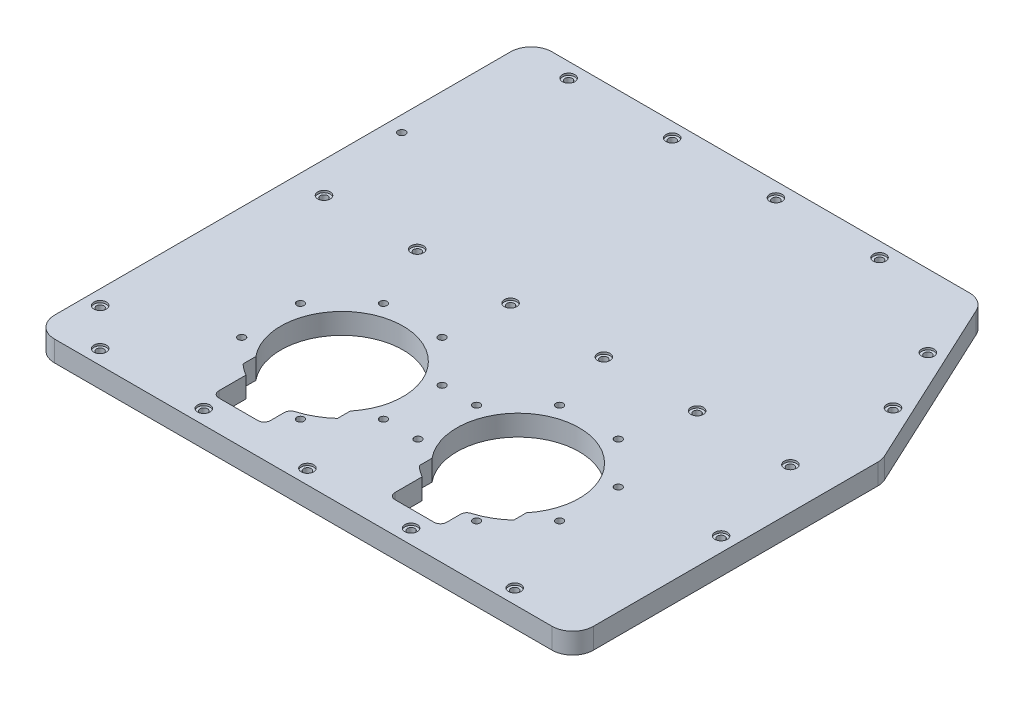
SolidWorks part; units mm, degrees
ref_plane "前视基准面" through (0, 0, 0) normal (0, 0, 1) x (1, 0, 0)
ref_plane "上视基准面" through (0, 0, 0) normal (0, 1, 0) x (1, 0, 0)
ref_plane "右视基准面" through (0, 0, 0) normal (1, 0, 0) x (0, 0, -1)
other "Configuration Table"
sketch "草图1" plane through (0, 0, 0) normal (0, 1, 0) x (1, 0, 0)
  line L0 (10, 0) -> (250, 0)
  line L1 (260, 10) -> (260, 147.1523)
  line L2 (211.3675, 240) -> (10, 240)
  line L3 (0, 230) -> (0, 10)
  line L4 (220.4305, 234.2262) -> (259.0631, 151.3785)
  line L5 (130, -24.4626) -> (130, 192.9738) construction
  arc A0 (0, 230) -> (10, 240) centre (10, 230) cw
  arc A1 (10, 0) -> (0, 10) centre (10, 10) cw
  arc A2 (250, 0) -> (260, 10) centre (250, 10) ccw
  arc A3 (211.3675, 240) -> (220.4305, 234.2262) centre (211.3675, 230) cw
  arc A4 (260, 147.1523) -> (259.0631, 151.3785) centre (250, 147.1523) ccw
  point P10 (0, 240)
  point P13 (0, 0)
  point P16 (260, 0)
  point P19 (217.7382, 240)
  point P22 (260, 149.3692)
  dimension "D5" = 10
  dimension "D6" = 10
  dimension "D7" = 10
  dimension "D8" = 10
  dimension "D9" = 10
  dimension "D1" = 25
  dimension "D2" = 260
  dimension "D3" = 240
  dimension "D4" = 100
extrude "凸台-拉伸1" add sketch "草图1" along normal blind 10
sketch "草图2" plane through (0, 10, 0) normal (0, 1, 0) x (1, 0, 0)
  line L0 (130, 0) -> (130, 158.5881) construction
  line L1 (88.6361, 0) -> (173.6361, 0)
  line L2 (10, 0) -> (250, 0) construction
  line L13 (88.6361, 0) -> (88.6361, 240) construction
  line L14 (211.3675, 240) -> (10, 240) construction
  line L15 (88.6361, 60) -> (59.1361, 60) construction
  line L16 (54.4526, 45.8407) -> (88.6361, 60) construction
  line L17 (65.8523, 35.101) -> (88.6361, 60) construction
  line L18 (111.4199, 35.101) -> (88.6361, 60) construction
  line L19 (65.8523, 35.101) -> (65.8523, 41.261)
  line L20 (111.4199, 35.101) -> (111.4199, 41.261)
  line L21 (150.8523, 35.101) -> (150.8523, 41.261)
  line L22 (88.6361, 15) -> (93.1361, 15)
  line L23 (96.1361, 18) -> (96.1361, 24.7819)
  line L24 (88.6361, 15) -> (74.2261, 15)
  line L25 (71.2261, 18) -> (71.2261, 31.0871)
  line L26 (196.4199, 35.101) -> (196.4199, 41.261)
  line L27 (173.6361, 15) -> (178.1361, 15)
  line L28 (181.1361, 18) -> (181.1361, 24.7819)
  line L29 (173.6361, 15) -> (159.2261, 15)
  line L30 (156.2261, 18) -> (156.2261, 31.0871)
  line L31 (173.6361, 60) -> (144.1361, 60) construction
  line L32 (139.4526, 45.8407) -> (173.6361, 60) construction
  line L33 (150.8523, 35.101) -> (173.6361, 60) construction
  line L34 (196.4199, 35.101) -> (173.6361, 60) construction
  arc A26 (111.4199, 41.261) -> (65.8523, 41.261) centre (88.6361, 60) ccw
  circle A27 centre (88.6361, 60) radius 37 construction
  circle A28 centre (54.4526, 45.8407) radius 1.75
  circle A29 centre (54.4526, 74.1593) radius 1.75
  circle A30 centre (74.4768, 94.1835) radius 1.75
  circle A31 centre (102.7954, 94.1835) radius 1.75
  circle A32 centre (122.8197, 74.1593) radius 1.75
  circle A33 centre (122.8197, 45.8407) radius 1.75
  circle A34 centre (102.7954, 25.8165) radius 1.75
  circle A35 centre (74.4768, 25.8165) radius 1.75 construction
  arc A36 (65.8523, 35.101) -> (71.2261, 31.0871) centre (88.6361, 60) ccw
  arc A37 (74.2261, 15) -> (71.2261, 18) centre (74.2261, 18) cw
  arc A38 (93.1361, 15) -> (96.1361, 18) centre (93.1361, 18) ccw
  arc A39 (98.279, 27.6569) -> (111.4199, 35.101) centre (88.6361, 60) ccw
  arc A40 (98.279, 27.6569) -> (96.1361, 24.7819) centre (99.1361, 24.7819) ccw
  arc A41 (196.4199, 41.261) -> (150.8523, 41.261) centre (173.6361, 60) ccw
  circle A42 centre (139.4526, 45.8407) radius 1.75
  circle A43 centre (139.4526, 74.1593) radius 1.75
  circle A44 centre (159.4768, 94.1835) radius 1.75
  circle A45 centre (187.7954, 94.1835) radius 1.75
  circle A46 centre (207.8197, 74.1593) radius 1.75
  circle A47 centre (207.8197, 45.8407) radius 1.75
  circle A48 centre (187.7954, 25.8165) radius 1.75
  arc A49 (150.8523, 35.101) -> (156.2261, 31.0871) centre (173.6361, 60) ccw
  arc A50 (159.2261, 15) -> (156.2261, 18) centre (159.2261, 18) cw
  arc A51 (178.1361, 15) -> (181.1361, 18) centre (178.1361, 18) ccw
  arc A52 (183.279, 27.6569) -> (196.4199, 35.101) centre (173.6361, 60) ccw
  arc A53 (183.279, 27.6569) -> (181.1361, 24.7819) centre (184.1361, 24.7819) ccw
  circle A54 centre (173.6361, 60) radius 37 construction
  circle A55 centre (159.4768, 25.8165) radius 1.75 construction
  point P31 (88.6361, 60)
  point P43 (96.1361, 15)
  point P45 (96.1361, 27.0939)
  point P70 (173.6361, 60)
  dimension "D2" = 59
  dimension "D3" = 74
  dimension "D7" = 42.46
  dimension "D8" = 3.5
  dimension "D12" = 3
  dimension "D13" = 3
  dimension "D11" = 17.41
  dimension "D15" = 3
  dimension "D1" = 85
  dimension "D5" = 22.5
  dimension "D6" = 60
  dimension "D9" = 7.5
  dimension "D10" = 7.5
  dimension "D14" = 45
  dimension "D16" = 2
  dimension "D4" = 8
extrude "切除-拉伸1" cut sketch "草图2" against normal through all contours A40 A39 L20 A26 L19 A36 L25 A37 L24 L22 A38 L23 | A30 | A31 | A33 | A34 | A28 | A29 | A53 A52 L26 A41 L21 A49 L30 A50 L29 L27 A51 L28 | A47 | A48 | A32 | A42 | A43 | A44 | A45 | A46
sketch "草图3" plane through (0, 10, 0) normal (0, 1, 0) x (1, 0, 0)
  line L0 (211.3675, 233) -> (10, 233) construction
  line L1 (7, 230) -> (7, 10) construction
  line L2 (10, 7) -> (250, 7) construction
  line L3 (253, 10) -> (253, 147.1523) construction
  line L4 (252.7189, 148.4201) -> (214.0864, 231.2679) construction
  line L5 (0, 230) -> (0, 10)
  line L6 (10, 0) -> (250, 0)
  line L7 (260, 10) -> (260, 147.1523)
  line L8 (259.0631, 151.3785) -> (220.4305, 234.2262)
  line L9 (211.3675, 240) -> (10, 240)
  line L10 (0, 230) -> (0, 10) construction
  line L11 (10, 0) -> (250, 0) construction
  line L12 (260, 10) -> (260, 147.1523) construction
  line L13 (259.0631, 151.3785) -> (220.4305, 234.2262) construction
  line L14 (211.3675, 240) -> (10, 240) construction
  arc A0 (10, 233) -> (7, 230) centre (10, 230) ccw construction
  arc A1 (7, 10) -> (10, 7) centre (10, 10) ccw construction
  arc A2 (250, 7) -> (253, 10) centre (250, 10) ccw construction
  arc A3 (253, 147.1523) -> (252.7189, 148.4201) centre (250, 147.1523) ccw construction
  arc A4 (214.0864, 231.2679) -> (211.3675, 233) centre (211.3675, 230) ccw construction
  arc A5 (10, 240) -> (0, 230) centre (10, 230) ccw
  arc A6 (0, 10) -> (10, 0) centre (10, 10) ccw
  arc A7 (250, 0) -> (260, 10) centre (250, 10) ccw
  arc A8 (260, 147.1523) -> (259.0631, 151.3785) centre (250, 147.1523) ccw
  arc A9 (220.4305, 234.2262) -> (211.3675, 240) centre (211.3675, 230) ccw
  arc A10 (10, 240) -> (0, 230) centre (10, 230) ccw construction
  arc A11 (0, 10) -> (10, 0) centre (10, 10) ccw construction
  arc A12 (250, 0) -> (260, 10) centre (250, 10) ccw construction
  arc A13 (260, 147.1523) -> (259.0631, 151.3785) centre (250, 147.1523) ccw construction
  arc A14 (220.4305, 234.2262) -> (211.3675, 240) centre (211.3675, 230) ccw construction
  circle A15 centre (25, 7) radius 1.8
  circle A21 centre (75, 7) radius 1.8
  circle A22 centre (125, 7) radius 1.8
  circle A23 centre (175, 7) radius 1.8
  circle A24 centre (225, 7) radius 1.8
  circle A25 centre (25, 233) radius 1.8
  circle A26 centre (75, 233) radius 1.8
  circle A27 centre (125, 233) radius 1.8
  circle A28 centre (175, 233) radius 1.8
  circle A30 centre (253, 78.5761) radius 1.8
  circle A31 centre (7, 25) radius 1.8
  circle A32 centre (226.3353, 205) radius 1.8
  circle A33 centre (241.0383, 173.4694) radius 1.8
  dimension "D3" = 3.6
  dimension "D4" = 5
  dimension "D6" = 3.6
  dimension "D9" = 3.6
  dimension "D10" = 3.6
  dimension "D11" = 3.6
  dimension "D13" = 3.6
  dimension "D5" = 25
  dimension "D7" = 25
  dimension "D12" = 25
  dimension "D14" = 35
  dimension "D1" = 0
  dimension "D2" = 7
  dimension "D8" = 4
extrude "切除-拉伸2" cut sketch "草图3" against normal through all
sketch "草图4" plane through (0, 10, 0) normal (0, 1, 0) x (1, 0, 0)
  line L0 (110.6837, 240) -> (110.6837, 0) construction
  line L1 (211.3675, 240) -> (10, 240) construction
  line L2 (10, 0) -> (250, 0) construction
  line L3 (110.6837, 120) -> (260, 120) construction
  line L4 (260, 10) -> (260, 147.1523) construction
  line L5 (260, 120) -> (260, 130) construction
  line L6 (260, 130) -> (0, 130) construction
  line L7 (0, 230) -> (0, 10) construction
  line L8 (0, 130) -> (0, 120) construction
  line L9 (0, 120) -> (110.6837, 120) construction
  line L11 (15, 125) -> (250, 125) construction
  circle A0 centre (15, 125) radius 1.8
  circle A2 centre (60, 125) radius 1.8
  circle A3 centre (105, 125) radius 1.8
  circle A4 centre (150, 125) radius 1.8
  circle A5 centre (195, 125) radius 1.8
  circle A6 centre (240, 125) radius 1.8
  dimension "D2" = 3.6
  dimension "D4" = 260
  dimension "D1" = 10
  dimension "D3" = 15
  dimension "D5" = 10
  dimension "D6" = 6
extrude "切除-拉伸3" cut sketch "草图4" against normal up to next
sketch "草图5" plane through (0, 0, 0) normal (0, -1, 0) x (1, 0, 0)
  circle A0 centre (25, -7) radius 3
  circle A1 centre (75, -7) radius 3
  circle A2 centre (125, -7) radius 3
  circle A3 centre (175, -7) radius 3
  circle A4 centre (225, -7) radius 3
  circle A5 centre (15, -125) radius 3
  circle A9 centre (60, -125) radius 3
  circle A10 centre (150, -125) radius 3
  circle A11 centre (105, -125) radius 3
  circle A12 centre (240, -125) radius 3
  circle A13 centre (195, -125) radius 3
  circle A14 centre (25, -233) radius 3
  circle A15 centre (75, -233) radius 3
  circle A16 centre (125, -233) radius 3
  circle A17 centre (175, -233) radius 3
  circle A18 centre (226.3353, -205) radius 3
  circle A19 centre (241.0383, -173.4694) radius 3
  circle A20 centre (253, -78.5761) radius 3
  circle A21 centre (7, -25) radius 3
  dimension "D1" = 6
extrude "切除-拉伸4" cut sketch "草图5" against normal blind 1
ref_plane "对称面" through (0, 5, 0) normal (0, -1, 0) x (-1, 0, 0)
mirror "镜向1" about plane through (0, 5, 0) normal (0, -1, 0) of "切除-拉伸4"
sketch "草图8" plane through (0, 0, 0) normal (0, -1, 0) x (1, 0, 0)
  line L0 (1012.5582, -307.7802) -> (51.2249, -307.7802) construction
  line L1 (22.0739, -172.0978) -> (15.2313, -200.6822)
  line L2 (15.2313, -200.6822) -> (22.0739, -200.6822)
  line L3 (22.0739, -200.6822) -> (24.6853, -189.7736)
  line L4 (24.6853, -189.7736) -> (38.1871, -189.7736)
  line L5 (38.1871, -189.7736) -> (39.6622, -183.6118)
  line L6 (39.6622, -183.6118) -> (26.0544, -183.6118)
  line L7 (26.0544, -183.6118) -> (28.8107, -172.0978)
  line L8 (28.8107, -172.0978) -> (22.0739, -172.0978)
  line L9 (44.809, -172.0978) -> (38.1871, -200.6822)
  line L10 (38.1871, -200.6822) -> (44.809, -200.6822)
  line L11 (44.809, -200.6822) -> (51.4309, -172.0978)
  line L12 (51.4309, -172.0978) -> (44.809, -172.0978)
  line L13 (53.7485, -194.3914) -> (48.1199, -200.6822)
  line L14 (48.1199, -200.6822) -> (71.6276, -200.6822)
  line L15 (53.7485, -194.3914) -> (71.6276, -194.3914)
  line L16 (72.3455, -189.7736) -> (58.8254, -189.7736)
  line L17 (60.6078, -183.2461) -> (73.7802, -183.2461)
  line L18 (61.6512, -178.4206) -> (86.7786, -178.4206)
  line L19 (86.7786, -178.4206) -> (92.1692, -198.6355)
  line L20 (101.0651, -199.1123) -> (122.961, -172.0978)
  line L21 (122.961, -172.0978) -> (114.7913, -172.0978)
  line L22 (114.7913, -172.0978) -> (97.9214, -193.4612)
  line L23 (97.9214, -193.4612) -> (95.2158, -183.6118)
  line L24 (95.2158, -183.6118) -> (102.0062, -183.6118)
  line L25 (102.0062, -183.6118) -> (106.8159, -177.521)
  line L26 (106.8159, -177.521) -> (93.5182, -177.521)
  line L27 (93.5182, -177.521) -> (92.0285, -172.0978)
  line L28 (92.0285, -172.0978) -> (62.5469, -172.0978)
  line L29 (125.6163, -172.0978) -> (120.806, -178.4206)
  line L30 (120.806, -178.4206) -> (139.5333, -178.4206)
  line L31 (141.2591, -182.2047) -> (136.8689, -200.6822)
  line L32 (136.8689, -200.6822) -> (143.4676, -200.6822)
  line L33 (143.4676, -200.6822) -> (147.9743, -181.7143)
  line L34 (140.5242, -172.0978) -> (125.6163, -172.0978)
  line L35 (161.9965, -172.0978) -> (186.1154, -172.0978)
  line L36 (186.1154, -172.0978) -> (181.4455, -178.4206)
  line L37 (181.4455, -178.4206) -> (165.1268, -178.4206)
  line L38 (152.5797, -194.3914) -> (147.201, -200.6822)
  line L39 (147.201, -200.6822) -> (170.4369, -200.6822)
  line L40 (166.9228, -194.3914) -> (152.5797, -194.3914)
  line L41 (175.3548, -189.3936) -> (159.1479, -189.3936)
  line L42 (174.3633, -183.6118) -> (160.2106, -183.2461)
  circle A0 centre (158.545, -177.3653) radius 2.2639
  circle A1 centre (158.545, -177.3653) radius 4.908
  circle A2 centre (173.6606, -195.3058) radius 2.2639
  circle A3 centre (173.6606, -195.3058) radius 4.908
  spline S0 degree 2 poles (139.5333, -178.4206) (142.1306, -179.2529) (141.2591, -182.2047) knots 0 0 0 1 1 1
  spline S1 degree 3 poles (140.5242, -172.0978) (141.5821, -172.2356) (143.0887, -172.9263) (144.7491, -173.9827) (145.9086, -174.7776) (146.3929, -175.8386) (147.2085, -176.4585) (147.3791, -177.2853) (147.7573, -178.1411) (148.1212, -179.6726) (147.902, -180.9291) (147.9743, -181.7143) knots 0 0 0 0 0.234104 0.362839 0.441119 0.539992 0.615492 0.655852 0.722699 0.824656 1 1 1 1
  spline S2 degree 3 poles (166.9228, -194.3914) (166.3546, -195.5942) (167.0977, -196.7577) (167.4997, -198.3175) (168.0436, -198.9936) (168.7135, -200.1011) (169.8684, -200.3837) (170.4369, -200.6822) knots 0 0 0 0 0.407752 0.516739 0.604038 0.735732 1 1 1 1
  spline S3 degree 3 poles (160.2106, -183.2461) (159.0039, -183.3159) (157.0311, -183.8378) (154.6008, -182.7428) (152.8228, -180.9622) (152.2741, -179.1395) (152.2406, -178.007) knots 0 0 0 0 0.335355 0.510172 0.694455 1 1 1 1
  spline S4 degree 3 poles (152.2406, -178.007) (151.7565, -179.2868) (151.0503, -181.6674) (152.2957, -184.4757) (152.9277, -186.7313) (155.5607, -188.4279) (157.3612, -189.6477) (159.1479, -189.3936) knots 0 0 0 0 0.272095 0.424694 0.579586 0.697268 1 1 1 1
  spline S5 degree 3 poles (174.3633, -183.6118) (175.5704, -183.559) (177.3983, -184.5588) (179.9403, -186.7301) (181.5256, -190.655) (180.9932, -193.9596) (180.1119, -195.6228) knots 0 0 0 0 0.224398 0.38873 0.637989 1 1 1 1
  spline S6 degree 3 poles (175.3548, -189.3936) (176.2463, -189.6557) (177.7024, -190.0661) (179.7177, -192.1951) (180.2057, -194.1862) (180.1119, -195.6228) knots 0 0 0 0 0.330461 0.500356 1 1 1 1
  spline S7 degree 3 poles (92.1692, -198.6355) (92.8883, -199.5584) (94.3699, -200.677) (97.7705, -201.3063) (99.8925, -200.0529) (101.0651, -199.1123) knots 0 0 0 0 0.346245 0.532188 1 1 1 1
  spline S8 degree 3 poles (72.3455, -189.7736) (73.4697, -189.7052) (73.8979, -191.2818) (73.7378, -193.7918) (72.0844, -193.9704) (71.6276, -194.3914) knots 0 0 0 0 0.391664 0.698151 1 1 1 1
  spline S9 degree 3 poles (73.7802, -183.2461) (75.0881, -183.3954) (76.7597, -184.4579) (79.1635, -186.2074) (80.0108, -188.6544) (80.5214, -191.3745) (80.1516, -194.0472) (78.8806, -196.7695) (76.8404, -198.518) (74.3591, -200.0196) (72.6363, -200.3603) (71.6276, -200.6822) knots 0 0 0 0 0.151326 0.234202 0.34478 0.445071 0.563167 0.657545 0.795637 0.873868 1 1 1 1
  spline S10 degree 3 poles (61.6512, -178.4206) (60.7654, -178.5311) (59.2233, -180.0811) (58.7984, -182.644) (60.6078, -183.2461) knots 0 0 0 0 0.381798 1 1 1 1
  spline S11 degree 3 poles (62.5469, -172.0978) (60.8548, -172.0783) (58.321, -172.8601) (55.5836, -174.9784) (53.9563, -177.1849) (53.0496, -179.7335) (52.7662, -182.4321) (53.0845, -185.0995) (54.9932, -188.0549) (57.3593, -189.1724) (58.8254, -189.7736) knots 0 0 0 0 0.194489 0.297456 0.396978 0.508302 0.606622 0.710402 0.813271 1 1 1 1
  spline S12 degree 3 poles (161.9965, -172.0978) (162.7119, -172.4139) (164.0747, -173.1288) (165.0432, -175.5782) (165.2365, -177.2867) (165.1268, -178.4206) knots 0 0 0 0 0.319161 0.557979 1 1 1 1
extrude "凸台-拉伸3" add sketch "草图8" along normal blind 2
sketch "草图9" plane through (0, 10, 0) normal (0, 1, 0) x (1, 0, 0)
  circle A0 centre (7.5, 170) radius 1.8
  dimension "D1" = 3.6
extrude "切除-拉伸5" cut sketch "草图9" against normal up to next
sketch "草图10" plane through (0, 0, 0) normal (0, -1, 0) x (1, 0, 0)
  circle A0 centre (7.5, -170) radius 3
  dimension "D1" = 6
extrude "切除-拉伸6" cut sketch "草图10" against normal blind 1
